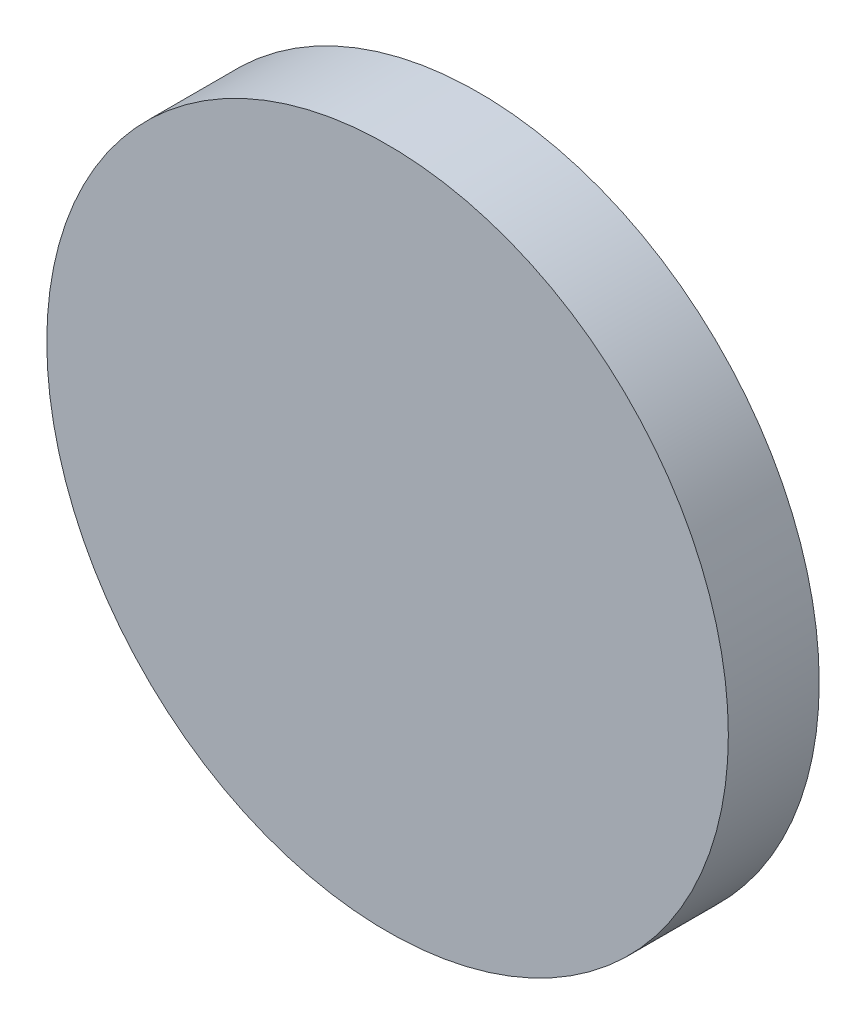
SolidWorks part; units mm, degrees
ref_plane "Front Plane" through (0, 0, 0) normal (0, 0, 1) x (1, 0, 0)
ref_plane "Top Plane" through (0, 0, 0) normal (0, 1, 0) x (1, 0, 0)
ref_plane "Right Plane" through (0, 0, 0) normal (1, 0, 0) x (0, 0, -1)
sketch "Sketch1" plane through (0, 0, 0) normal (0, 0, 1) x (1, 0, 0)
  circle A0 centre (0, 0) radius 190.5
  dimension "D1" = 381
extrude "Boss-Extrude1" add sketch "Sketch1" along normal blind 50.8
sketch "Sketch3" plane through (0, 0, 0) normal (0, 0, -1) x (-1, 0, 0)
  circle A0 centre (0, 0) radius 63.5
  dimension "D1" = 127
extrude "Cut-Extrude2" cut sketch "Sketch3" against normal blind 25.4
